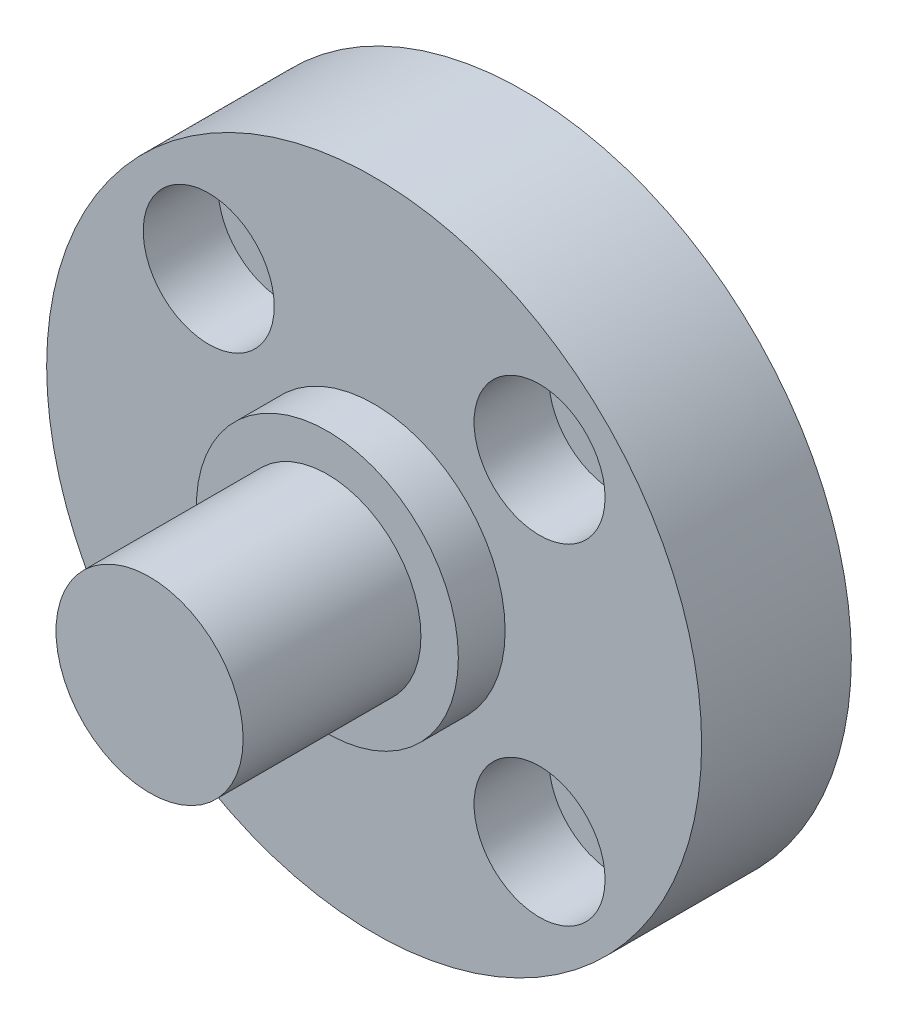
SolidWorks part; units mm, degrees
material "5052-H34"
ref_plane "正面" through (0, 0, 0) normal (0, 0, 1) x (1, 0, 0)
ref_plane "平面" through (0, 0, 0) normal (0, 1, 0) x (1, 0, 0)
ref_plane "右側面" through (0, 0, 0) normal (1, 0, 0) x (0, 0, -1)
sketch "ｽｹｯﾁ1" plane through (0, 0, 0) normal (0, 0, 1) x (1, 0, 0)
  circle A0 centre (0, 0) radius 17.5
  dimension "D1" = 35
extrude "ﾎﾞｽ - 押し出し1" add sketch "ｽｹｯﾁ1" along normal blind 8
sketch "ｽｹｯﾁ2" plane through (0, 0, 8) normal (0, 0, 1) x (1, 0, 0)
  circle A0 centre (0, 0) radius 7
  dimension "D1" = 14
extrude "ﾎﾞｽ - 押し出し2" add sketch "ｽｹｯﾁ2" along normal blind 2.5
sketch "ｽｹｯﾁ3" plane through (0, 0, 10.5) normal (0, 0, 1) x (1, 0, 0)
  circle A0 centre (0, 0) radius 5
  dimension "D1" = 10
extrude "ﾎﾞｽ - 押し出し3" add sketch "ｽｹｯﾁ3" along normal blind 9.5
sketch "ｽｹｯﾁ4" plane through (0, 0, 8) normal (0, 0, 1) x (1, 0, 0)
  line L1 (-8.8388, 8.8388) -> (8.8388, 8.8388) construction
  line L2 (-8.8388, 8.8388) -> (-8.8388, -8.8388) construction
  line L3 (-8.8388, -8.8388) -> (8.8388, -8.8388) construction
  line L4 (8.8388, 8.8388) -> (8.8388, -8.8388) construction
  line L5 (-8.8388, 8.8388) -> (8.8388, -8.8388) construction
  line L6 (-8.8388, -8.8388) -> (8.8388, 8.8388) construction
  circle A0 centre (8.8388, 8.8388) radius 1.6
  circle A1 centre (8.8388, -8.8388) radius 1.6
  circle A2 centre (-8.8388, -8.8388) radius 1.6
  circle A3 centre (-8.8388, 8.8388) radius 1.6
  point P0 (0, 0)
  dimension "D2" = 3.2
  dimension "D1" = 25
extrude "ｶｯﾄ - 押し出し1" cut sketch "ｽｹｯﾁ4" against normal through all
sketch "ｽｹｯﾁ5" plane through (0, 0, 8) normal (0, 0, 1) x (1, 0, 0)
  circle A0 centre (-8.8388, -8.8388) radius 1.6 construction
  circle A1 centre (8.8388, -8.8388) radius 1.6 construction
  circle A2 centre (8.8388, 8.8388) radius 1.6 construction
  circle A3 centre (-8.8388, 8.8388) radius 1.6 construction
  circle A4 centre (-8.8388, -8.8388) radius 1.6
  circle A5 centre (8.8388, -8.8388) radius 1.6
  circle A6 centre (8.8388, 8.8388) radius 1.6
  circle A7 centre (-8.8388, 8.8388) radius 1.6
  circle A8 centre (8.8388, 8.8388) radius 3.5
  circle A9 centre (8.8388, -8.8388) radius 3.5
  circle A10 centre (-8.8388, -8.8388) radius 3.5
  circle A11 centre (-8.8388, 8.8388) radius 3.5
  dimension "D1" = 7
extrude "ｶｯﾄ - 押し出し2" cut sketch "ｽｹｯﾁ5" against normal blind 4
